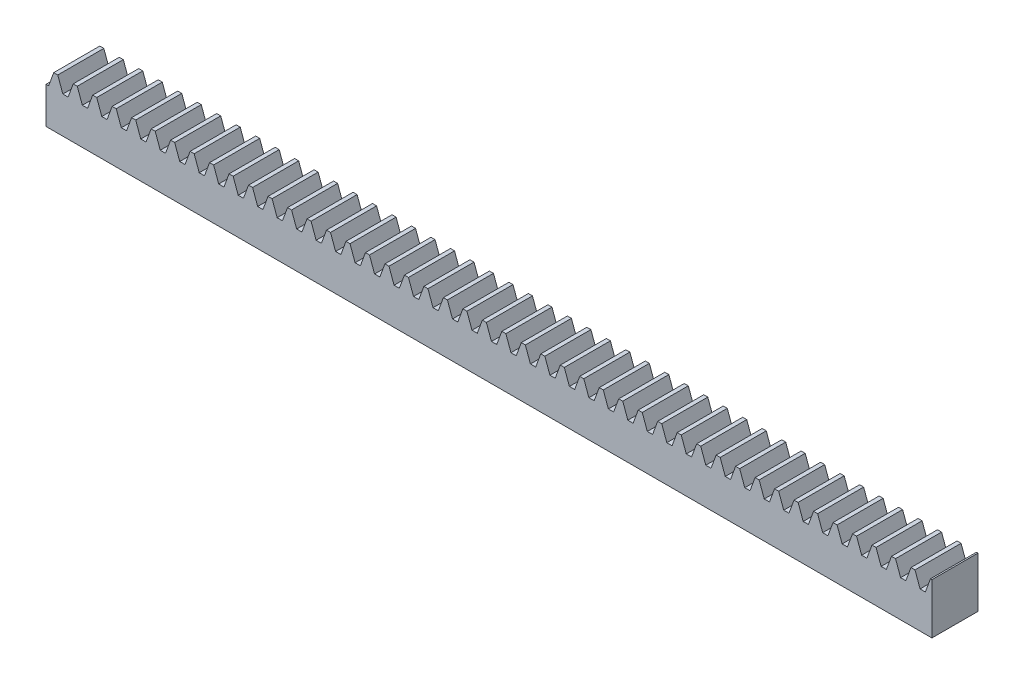
SolidWorks part; units mm, degrees
extrude "Blank" add sketch "BlankSke" against normal blind 520
sketch "BlankSke" plane through (0, 0, 0) normal (0, 0, 1) x (1, 0, 0)
  line L1 (0, 0) -> (10000, 0)
  line L2 (0, 0) -> (0, 570)
  line L3 (0, 570) -> (10000, 570)
  line L4 (10000, 0) -> (10000, 570)
  dimension "Length" = 10000
  dimension "Blank_height" = 570
ref_plane "Plane1" through (0, 0, 0) normal (0, 0, 1) x (1, 0, 0)
ref_plane "Plane2" through (0, 0, 0) normal (0, 1, 0) x (1, 0, 0)
ref_plane "Plane3" through (0, 0, 0) normal (1, 0, 0) x (0, 0, -1)
sketch "HoldingSke" plane through (0, 0, 0) normal (0, 1, 0) x (1, 0, 0)
  line L0 (0, 0) -> (0.002, 0.0141)
  line L1 (-15, 0) -> (100, 0) construction
  line L2 (0, 0) -> (-2.1039, 2.3779)
  line L3 (0, 0) -> (-11.863, 4.5341)
  line L4 (0, 0) -> (5.8897, 6.316)
  line L5 (0, 0) -> (-23.7986, -8.8762)
  line L6 (0, 0) -> (-10.5278, -7.1032)
  line L9 (-71.009, 38.7566) -> (9325.9172, 3458.958)
  line L10 (-76.2, 72.3779) -> (423.8, 72.3779)
  line L11 (0, 0) -> (-520, 0)
  line L12 (-76.2, 101.6) -> (-74, 101.6)
  line L13 (24.9733, 27.94) -> (52.9518, 28.4284)
  line L14 (24.9733, 27.94) -> (24.9743, 27.94)
  line L15 (24.9733, 27.94) -> (100.4006, 29.5858)
  circle A0 centre (0, 0) radius 19.05
  circle A1 centre (0, 0) radius 250
  circle A2 centre (0, 0) radius 12.7
  dimension "MPH" = 500
  dimension "Diameter" = 38.1
  dimension "Num_teeth" = 47
  dimension "Pitch" = 0.0143
  dimension "Show_teeth" = 998
  dimension "Thickness" = 12.7
  dimension "Ap" = 20
  dimension "Pitch_height" = 500
  dimension "Width" = 520
  dimension "Backlash" = 2.2
  dimension "Addendum_fac" = 1
  dimension "Dedendum_fac" = 1.25
  dimension "Clearance_fac" = 0.25
  dimension "Dedendum_add" = 0.001
  dimension "Length" = 10000
  dimension "Module" = 70
sketch "TooCutSkeIll" plane through (0, 0, 0) normal (0, 0, 1) x (1, 0, 0)
  line L0 (-86.3852, 568.1577) -> (-33.9217, 424.0153)
  line L1 (-17.4761, 412.5) -> (17.4761, 412.5)
  line L2 (33.9217, 424.0153) -> (86.3852, 568.1577)
  line L3 (10000, 570) -> (0, 570) construction
  line L4 (0, 0) -> (0, 64.897) construction
  line L5 (-13.208, 500) -> (12.954, 500) construction
  line L6 (0, 0) -> (10000, 0) construction
  line L7 (61.5779, 500) -> (61.5779, 48.7463) construction
  line L8 (-61.5779, 500) -> (-61.5779, 48.7463) construction
  line L9 (89.0164, 570) -> (89.0164, 570.0254)
  line L10 (-89.0164, 570) -> (-89.0164, 570.0254)
  line L11 (-89.0164, 570.0254) -> (89.0164, 570.0254)
  arc A0 (17.4761, 412.5) -> (33.9217, 424.0153) centre (17.4761, 430.001) ccw
  arc A1 (-33.9217, 424.0153) -> (-17.4761, 412.5) centre (-17.4761, 430.001) ccw
  arc A2 (89.0164, 570) -> (86.3852, 568.1577) centre (89.0164, 567.2) ccw
  arc A3 (-86.3852, 568.1577) -> (-89.0164, 570) centre (-89.0164, 567.2) ccw
  dimension "Pitch_height" = 500
  dimension "Addendum_plus" = 70.0254
  dimension "Pressure_angle" = 20
  dimension "Gap_width" = 123.1557
  dimension "Dedendum" = 87.5
extrude "ToothCutIll" [suppressed] cut sketch "TooCutSkeIll" against normal through all
sketch "TooCutSkeSim" plane through (0, 0, 0) normal (0, 0, 1) x (1, 0, 0)
  line L0 (29.7305, 412.5) -> (-29.7305, 412.5)
  line L1 (87.065, 570.0254) -> (29.7305, 412.5)
  line L2 (0, 17.4625) -> (0, 53.467) construction
  line L3 (87.065, 570.0254) -> (-87.065, 570.0254)
  line L6 (-87.065, 570.0254) -> (-29.7305, 412.5)
  line L9 (-61.5779, 500) -> (61.5779, 500) construction
  line L10 (0, 0) -> (10000, 0) construction
  line L11 (61.5779, 500) -> (61.5779, 53.467) construction
  line L12 (-61.5779, 500) -> (-61.5779, 53.467) construction
  dimension "Pitch_height" = 500
  dimension "Addendum_plus" = 70.0254
  dimension "Pressure_angle" = 20
  dimension "Gap_width" = 123.1557
  dimension "Dedendum" = 87.5
extrude "ToothCutSim" cut sketch "TooCutSkeSim" against normal through all
pattern_linear "TeethCuts" count 46 spacing 219.9115 along (1, 0, 0) of "ToothCutIll", "ToothCutSim"
sketch "Sketch1" plane through (0, 0, 0) normal (-1, 0, 0) x (0, 0, 1)
  line L0 (-520, 412.5) -> (0, 0) construction
  circle A0 centre (-260, 206.25) radius 127
extrude "Cut-Extrude1" cut sketch "Sketch1" against normal blind 127
equation "' \"Module@HoldingSke\" = 6.35"
equation "' \"Num_teeth@HoldingSke\" = 12"
equation "' \"Ap@HoldingSke\" =  20"
equation "' \"Ap@HoldingSke\" = 20"
equation "' \"Width@HoldingSke\" = 0.25 * 25.4"
equation "' \"Show_teeth@HoldingSke\" = 500"
equation "' \"Backlash@HoldingSke\" = 0.009 * 25.4"
equation "' \"Addendum_fac@HoldingSke\" = 1.0"
equation "' \"Dedendum_fac@HoldingSke\" = 1.25"
equation "' \"Dedendum_add@HoldingSke\" = 0.00005 * 25.4"
equation "' \"Clearance_fac@HoldingSke\" = 0.25"
equation "' \"Pitch_height@HoldingSke\" = 1 * 25.4"
equation "' \"Length@HoldingSke\" = 4.71 * 25.4"
equation "\"Pitch@HoldingSke\" = 1 / \"Module@HoldingSke\""
equation "\"MPH@HoldingSke\" = \"Dedendum_fac@HoldingSke\" / \"Pitch@HoldingSke\" + 2 * \"Dedendum_add@HoldingSke\" + 0.002 * 25.4"
equation "\"MPH@HoldingSke\" = ((sgn( \"MPH@HoldingSke\" - \"Pitch_height@HoldingSke\")+1)*( \"MPH@HoldingSke\" - \"Pitch_height@HoldingSke\"))/2 + \"Pitch_height@HoldingSke\""
equation "\"Blank_height@BlankSke\" = \"Pitch_height@HoldingSke\" + \"Addendum_fac@HoldingSke\"  / \"Pitch@HoldingSke\" "
equation "\"Length@BlankSke\" =  \"Length@HoldingSke\""
equation "\"Face_width@Blank\" = \"Width@HoldingSke\""
equation "\"Pressure_angle@TooCutSkeIll\" = \"Ap@HoldingSke\""
equation "\"Addendum_plus@TooCutSkeIll\" =  \"Addendum_fac@HoldingSke\"  / \"Pitch@HoldingSke\" + 0.001 *25.4"
equation "\"Dedendum@TooCutSkeIll\" = \"Dedendum_fac@HoldingSke\"  / \"Pitch@HoldingSke\""
equation "\"Pitch_height@TooCutSkeIll\" =  \"MPH@HoldingSke\""
equation "\"Gap_width@TooCutSkeIll\" = 3.14159265 / 2 / \"Pitch@HoldingSke\" + 6 * \"Backlash@HoldingSke\""
equation "\"Pressure_angle@TooCutSkeSim\" = \"Ap@HoldingSke\""
equation "\"Addendum_plus@TooCutSkeSim\" =  \"Addendum_fac@HoldingSke\"  / \"Pitch@HoldingSke\" + 0.001 * 25.4"
equation "\"Dedendum@TooCutSkeSim\" = \"Dedendum_fac@HoldingSke\"  / \"Pitch@HoldingSke\""
equation "\"Pitch_height@TooCutSkeSim\" =  \"MPH@HoldingSke\""
equation "\"Gap_width@TooCutSkeSim\" = 3.14159265 / 2 / \"Pitch@HoldingSke\" + 6 * \"Backlash@HoldingSke\""
equation "\"Root_fillet@TooCutSkeIll\" = \"Clearance_fac@HoldingSke\" / \"Pitch@HoldingSke\" + \"Dedendum_add@HoldingSke\""
equation "\"Break_rad@TooCutSkeIll\" = 0.02 / \"Pitch@HoldingSke\" * 2"
equation "\"Linear_pitch@TeethCuts\" = 3.14159265 / \"Pitch@HoldingSke\""
equation "\"Num_teeth@HoldingSke\" = int( ( \"Length@HoldingSke\" + 0 ) / (3.14159265 / \"Pitch@HoldingSke\")) + 0.9999  + 1"
equation " \"Num_teeth@TeethCuts\" = int( \"Show_teeth@HoldingSke\" ) + 1"
equation " \"Num_teeth@TeethCuts\" = ((sgn( \"Num_teeth@TeethCuts\" - \"Num_teeth@HoldingSke\" )-1)*( \"Num_teeth@TeethCuts\" - \"Num_teeth@HoldingSke\" ))/-2+ \"Num_teeth@HoldingSke\""
equation " \"Num_teeth@TeethCuts\" = ((sgn( \"Num_teeth@TeethCuts\" - 2.0)+1)*( \"Num_teeth@TeethCuts\" - 2.0))/2 +2.0"
